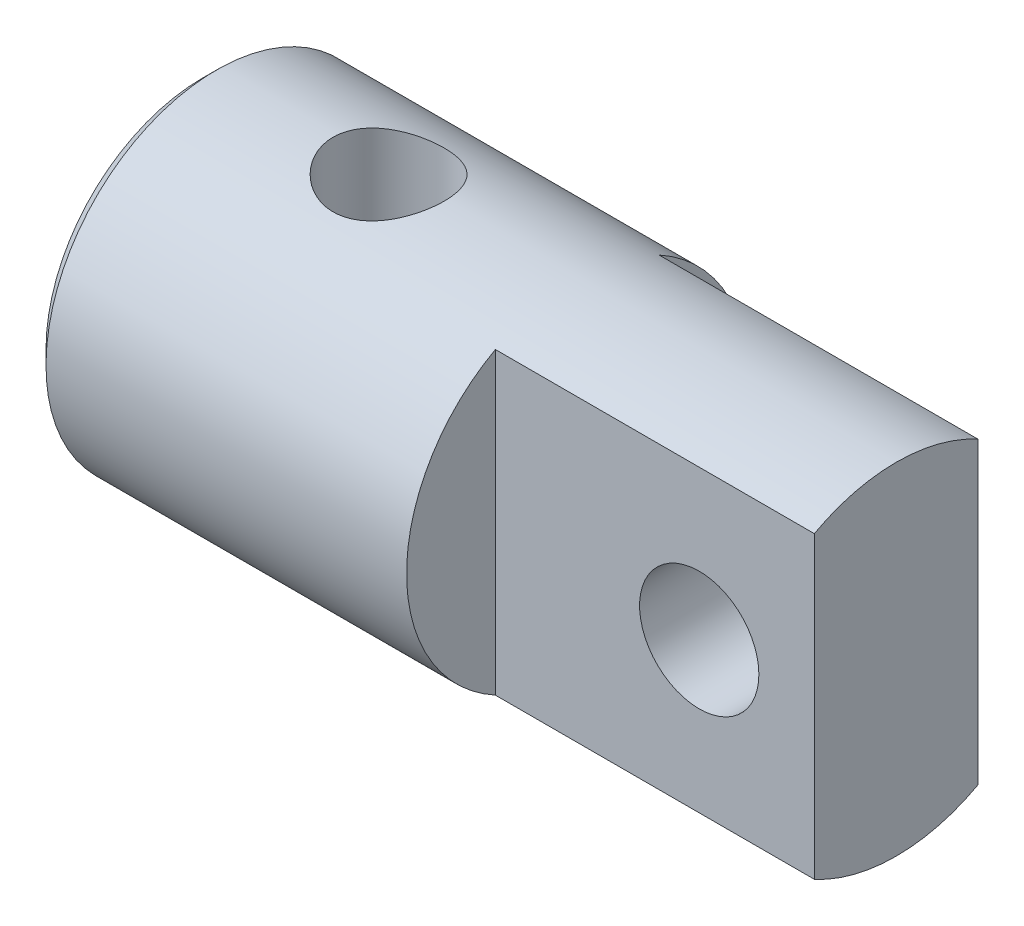
SolidWorks part; units mm, degrees
material "3003 Alloy"
ref_plane "Front Plane" through (0, 0, 0) normal (0, 0, 1) x (1, 0, 0)
ref_plane "Top Plane" through (0, 0, 0) normal (0, 1, 0) x (1, 0, 0)
ref_plane "Right Plane" through (0, 0, 0) normal (1, 0, 0) x (0, 0, -1)
sketch "Sketch1" plane through (0, 0, 0) normal (0, 0, 1) x (1, 0, 0)
  line L0 (0, 0) -> (0, 6.15)
  line L1 (0, 6.15) -> (25, 6.15)
  line L2 (25, 6.15) -> (25, 0)
  line L3 (25, 0) -> (0, 0)
  dimension "D1" = 6.15
  dimension "D2" = 25
revolve "Revolve1" add sketch "Sketch1" angle 360 about L3
chamfer "Chamfer1" distance 0.5 angle 45 1 edges at (0, 6.15, 0)
sketch "Sketch3" plane through (0, 0, 0) normal (0, 1, 0) x (1, 0, 0)
  circle A0 centre (6.7, 0) radius 2
  dimension "D3" = 4
  dimension "D1" = 6.7
  dimension "D2" = 6.15
extrude "Cut-Extrude1" cut sketch "Sketch3" against normal through all both and the other way through all
sketch "Sketch6" plane through (0, 0, 0) normal (0, 1, 0) x (1, 0, 0)
  line L0 (0.5, -6.15) -> (25, -6.15) construction
  line L1 (13.5, -6.15) -> (25, -6.15)
  line L2 (13.5, -6.15) -> (13.5, -2.95)
  line L3 (13.5, -2.95) -> (25, -2.95)
  line L4 (25, -6.15) -> (25, -2.95)
  line L5 (25, -6.15) -> (25, 6.15) construction
  line L6 (25, 6.15) -> (0.5, 6.15) construction
  line L7 (13.5, 6.15) -> (25, 6.15)
  line L8 (13.5, 6.15) -> (13.5, 2.95)
  line L9 (13.5, 2.95) -> (25, 2.95)
  line L10 (25, 6.15) -> (25, 2.95)
  dimension "D1" = 11.5
  dimension "D2" = 3.2
extrude "Cut-Extrude3" cut sketch "Sketch6" against normal through all both and the other way through all
sketch "Sketch11" plane through (0, 0, 0) normal (0, 0, 1) x (1, 0, 0)
  line L2 (8.7, -6.15) -> (25, -6.15) construction
  circle A0 centre (20.85, 0) radius 2.15
  dimension "D1" = 4.3
  dimension "D2" = 4.15
  dimension "D3" = 6.15
extrude "Cut-Extrude4" cut sketch "Sketch11" against normal through all both and the other way through all contours A0
